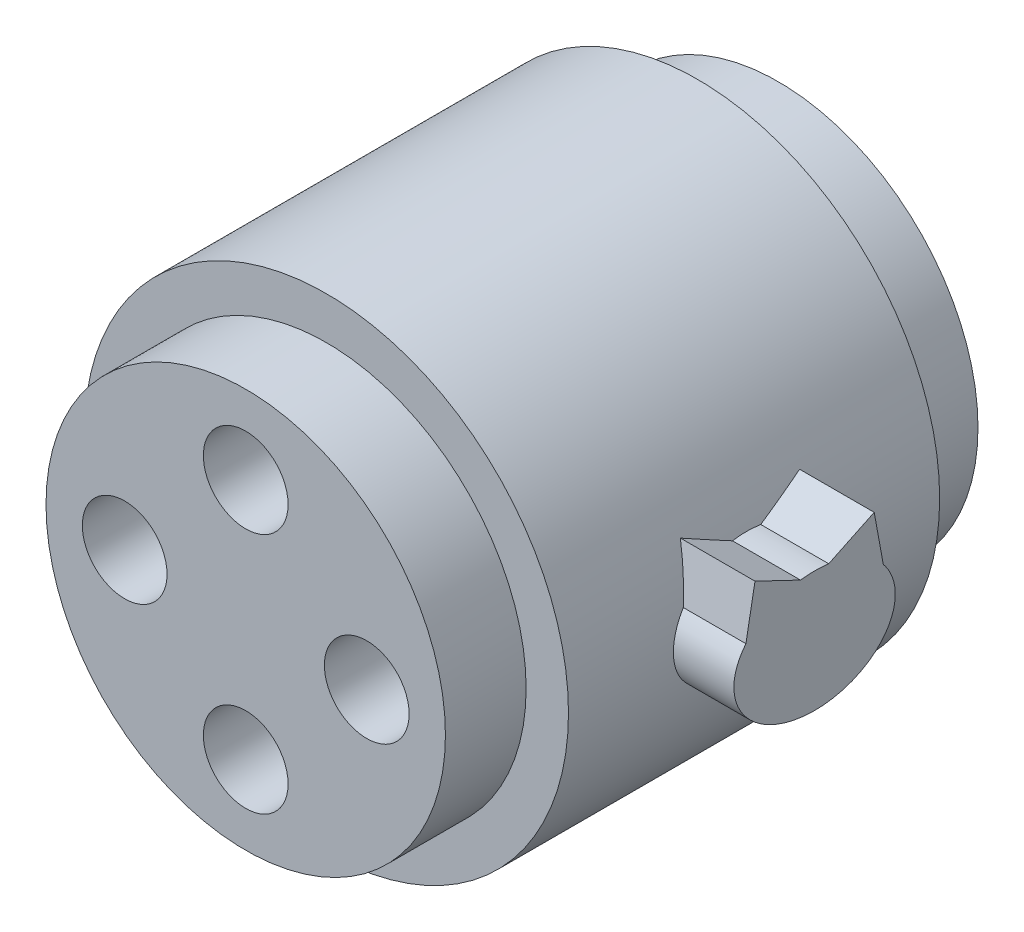
SolidWorks part; units mm, degrees
material "ABS"
ref_plane "前视基准面" through (0, 0, 0) normal (0, 0, 1) x (1, 0, 0)
ref_plane "上视基准面" through (0, 0, 0) normal (0, 1, 0) x (1, 0, 0)
ref_plane "右视基准面" through (0, 0, 0) normal (1, 0, 0) x (0, 0, -1)
other "Configuration Table"
sketch "草图1" plane through (0, 0, 0) normal (0, 0, 1) x (1, 0, 0)
  circle A0 centre (0, 0) radius 12
  dimension "D1" = 24
extrude "凸台-拉伸1" add sketch "草图1" along normal blind 18.4
sketch "草图2" plane through (0, 0, 18.4) normal (0, 0, 1) x (1, 0, 0)
  circle A0 centre (0, 0) radius 9.9
  dimension "D1" = 19.8
extrude "凸台-拉伸2" add sketch "草图2" along normal blind 4
sketch "草图3" plane through (0, 0, 0) normal (0, 0, -1) x (-1, 0, 0)
  circle A0 centre (0, 0) radius 9.9
  dimension "D1" = 19.8
extrude "凸台-拉伸3" add sketch "草图3" along normal blind 4
sketch "草图7" plane through (0, 0, 0) normal (1, 0, 0) x (0, 0, -1)
  line L0 (-22.4, 0) -> (4, 0) construction
  line L1 (-22.4, 9.9) -> (-22.4, -9.9) construction
  line L2 (4, -9.9) -> (4, 9.9) construction
  line L3 (-9.2, -3) -> (-9.2, -11.1707) construction
  line L4 (-12.1548, 4.0335) -> (-12.6049, 1.5744)
  line L5 (-12.1548, 4.0335) -> (-9.9, 2.9537)
  line L6 (-6.2452, 4.0335) -> (-8.5, 2.9537)
  line L7 (-6.2452, 4.0335) -> (-5.7951, 1.5744)
  ellipse E0 centre (-9.2, 0) end of major axis (-5.2, 0) minor radius 3 (-12.6049, 1.5744) -> (-5.7951, 1.5744) ccw
  ellipse E1 centre (-9.2, 0) end of major axis (-5.2, 0) minor radius 3 (-8.5, 2.9537) -> (-9.9, 2.9537) ccw
  dimension "D1" = 8
  dimension "D2" = 6
  dimension "D3" = 2.5
  dimension "D4" = 2.5
  dimension "D5" = 5
  dimension "D6" = 0.7
extrude "凸台-拉伸4" add sketch "草图7" along normal blind 15
sketch "草图4" plane through (0, 0, 22.4) normal (0, 0, 1) x (1, 0, 0)
  circle A0 centre (0, 0) radius 6 construction
  circle A1 centre (0, 6) radius 2.1
  circle A2 centre (6, 0) radius 2.1
  circle A3 centre (0, -6) radius 2.1
  circle A4 centre (-6, 0) radius 2.1
  point P14 (0, 0)
  dimension "D1" = 12
  dimension "D2" = 4.2
  dimension "D3" = 4
extrude "切除-拉伸1" cut sketch "草图4" against normal through all
